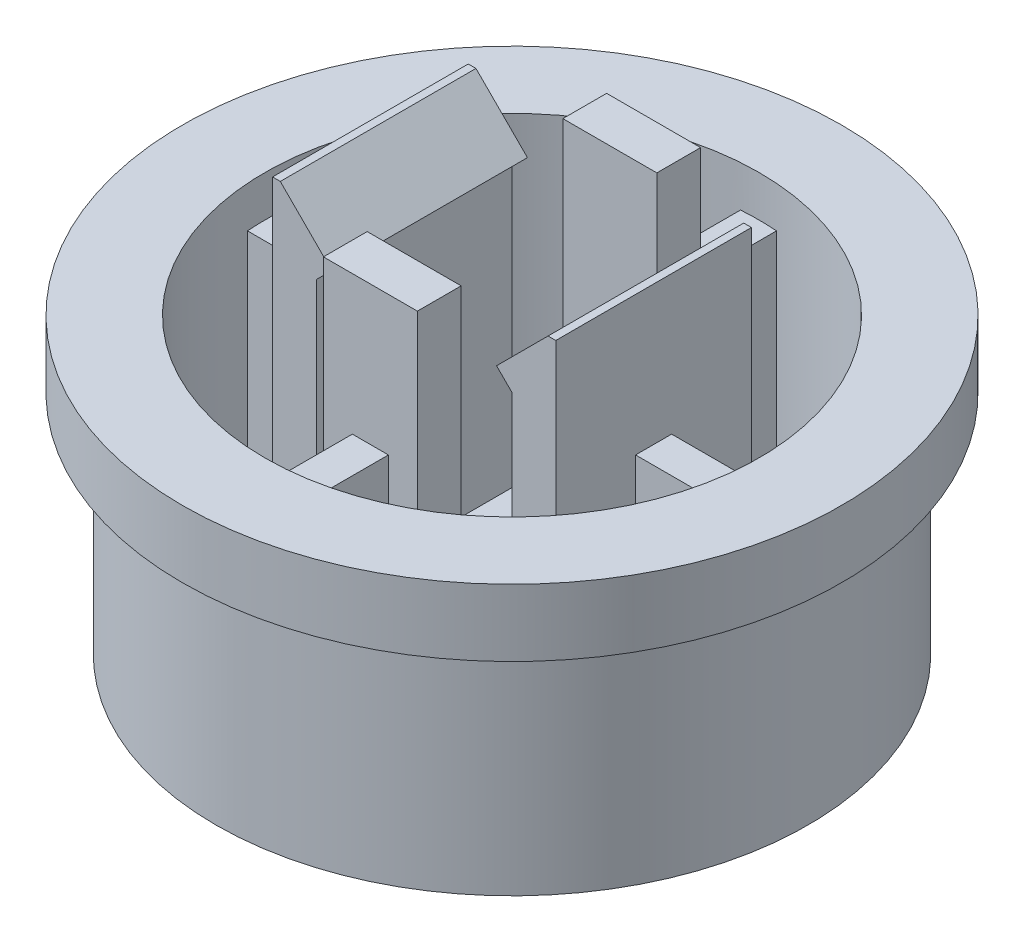
SolidWorks part; units mm, degrees
ref_plane "Front" through (0, 0, 0) normal (0, 0, 1) x (1, 0, 0)
ref_plane "Top" through (0, 0, 0) normal (0, 1, 0) x (1, 0, 0)
ref_plane "Right" through (0, 0, 0) normal (1, 0, 0) x (0, 0, -1)
sketch "Эскиз1" plane through (0, 0, 0) normal (0, 1, 0) x (1, 0, 0)
  circle A0 centre (0, 0) radius 5.75
extrude "Бобышка-Вытянуть1" add sketch "Эскиз1" along normal blind 0.9
sketch "Эскиз2" plane through (0, 0.9, 0) normal (0, 1, 0) x (1, 0, 0)
  circle A0 centre (0, 0) radius 5.75
  circle A1 centre (0, 0) radius 4.8
extrude "Бобышка-Вытянуть2" add sketch "Эскиз2" along normal blind 3.5
sketch "Эскиз3" plane through (0, 4.4, 0) normal (0, 1, 0) x (1, 0, 0)
  circle A0 centre (0, 0) radius 4.8
  circle A1 centre (0, 0) radius 6.4
extrude "Бобышка-Вытянуть3" add sketch "Эскиз3" along normal blind 1.3
sketch "Эскиз4" plane through (0, 0.9, 0) normal (0, 1, 0) x (1, 0, 0)
  line L2 (-2.75, -1.9) -> (-2.75, 1.9)
  line L4 (2.75, -1.9) -> (2.75, 1.9)
  line L8 (-1.9, -1.9) -> (-1.9, 1.9)
  line L10 (1.9, -1.9) -> (1.9, 1.9)
  line L11 (-0.9124, 1.9) -> (0.9124, 1.9)
  line L12 (-0.9124, 1.9) -> (-0.9124, 2.75)
  line L13 (-0.9124, 2.75) -> (0.9124, 2.75)
  line L14 (0.9124, 1.9) -> (0.9124, 2.75)
  line L15 (-0.9124, 1.9) -> (0.9124, 2.75) construction
  line L16 (-0.9124, 2.75) -> (0.9124, 1.9) construction
  line L17 (-1.9, 1.9) -> (-2.75, 1.9)
  line L18 (-0.9124, -2.75) -> (0.9124, -2.75)
  line L19 (-0.9124, -2.75) -> (-0.9124, -1.9)
  line L20 (-0.9124, -1.9) -> (0.9124, -1.9)
  line L21 (0.9124, -2.75) -> (0.9124, -1.9)
  line L22 (-0.9124, -2.75) -> (0.9124, -1.9) construction
  line L23 (-0.9124, -1.9) -> (0.9124, -2.75) construction
  line L24 (1.9, 1.9) -> (2.75, 1.9)
  line L25 (-1.9, -1.9) -> (-2.75, -1.9)
  line L26 (1.9, -1.9) -> (2.75, -1.9)
  point P0 (0, 0)
  point P6 (0, 0)
  point P15 (0, 2.325)
  point P22 (0, -2.325)
  dimension "D3" = 3.8
extrude "Бобышка-Вытянуть4" add sketch "Эскиз4" along normal blind 6.7
sketch "Эскиз5" plane through (0, 0, -1.9) normal (0, 0, -1) x (-1, 0, 0)
  line L9 (1.9, 7.6) -> (1.9, 0.9) construction
  line L10 (-1.9, 7.6) -> (-1.9, 0.9) construction
  line L11 (1.9, 6.3) -> (1.6, 6.6)
  line L12 (1.6, 6.6) -> (2.6, 7.6)
  line L13 (1.9, 7.6) -> (2.75, 7.6) construction
  line L14 (-1.9, 6.3) -> (-1.6, 6.6)
  line L15 (-1.6, 6.6) -> (-2.6, 7.6)
  line L16 (-2.75, 7.6) -> (-1.9, 7.6) construction
  line L17 (1.9, 6.3) -> (2.6, 7.6)
  line L18 (-1.9, 6.3) -> (-2.6, 7.6)
extrude "Бобышка-Вытянуть5" add sketch "Эскиз5" against normal blind 3.8
sketch "Эскиз6" plane through (0, 0, -1.9) normal (0, 0, -1) x (-1, 0, 0)
  line L0 (1.9, 6.9) -> (2.6, 7.6)
  line L1 (1.9, 7.6) -> (2.75, 7.6) construction
  line L2 (2.6, 7.6) -> (1.9, 7.6)
  line L3 (1.9, 7.6) -> (1.9, 6.9)
  line L4 (-1.9, 6.9) -> (-2.6, 7.6)
  line L5 (-2.75, 7.6) -> (-1.9, 7.6) construction
  line L6 (-2.6, 7.6) -> (-1.9, 7.6)
  line L7 (-1.9, 7.6) -> (-1.9, 6.9)
extrude "Вырез-Вытянуть1" cut sketch "Эскиз6" against normal up to next
sketch "Эскиз7" plane through (0, 0.9, 0) normal (0, 1, 0) x (1, 0, 0)
  line L0 (-0.35, -2.75) -> (0.35, -2.75)
  line L1 (4.7872, -0.35) -> (2.75, -0.35)
  line L2 (0.35, 2.75) -> (0.35, 4.7872)
  line L3 (4.7872, 0.35) -> (2.75, 0.35)
  line L4 (-0.35, 2.75) -> (-0.35, 4.7872)
  line L5 (-0.9124, -2.75) -> (0.9124, -2.75) construction
  line L6 (-0.9124, -2.75) -> (0.9124, -2.75) construction
  line L7 (-2.75, -0.35) -> (-4.7872, -0.35)
  line L8 (0.35, -4.7872) -> (0.35, -2.75)
  line L9 (-2.75, 0.35) -> (-4.7872, 0.35)
  line L10 (-0.35, -4.7872) -> (-0.35, -2.75)
  line L11 (-2.75, -0.35) -> (-2.75, 0.35)
  line L12 (-2.75, 1.9) -> (-2.75, -1.9) construction
  line L13 (-0.35, 2.75) -> (0.35, 2.75)
  line L14 (0.9124, 2.75) -> (-0.9124, 2.75) construction
  line L15 (2.75, -0.35) -> (2.75, 0.35)
  line L16 (2.75, -1.9) -> (2.75, 1.9) construction
  arc A0 (-0.35, -4.7872) -> (0.35, -4.7872) centre (0, 0) ccw
  arc A1 (-4.7872, 0.35) -> (-4.7872, -0.35) centre (0, 0) ccw
  arc A2 (0.35, 4.7872) -> (-0.35, 4.7872) centre (0, 0) ccw
  arc A3 (4.7872, -0.35) -> (4.7872, 0.35) centre (0, 0) ccw
extrude "Бобышка-Вытянуть6" add sketch "Эскиз7" along normal blind 4
